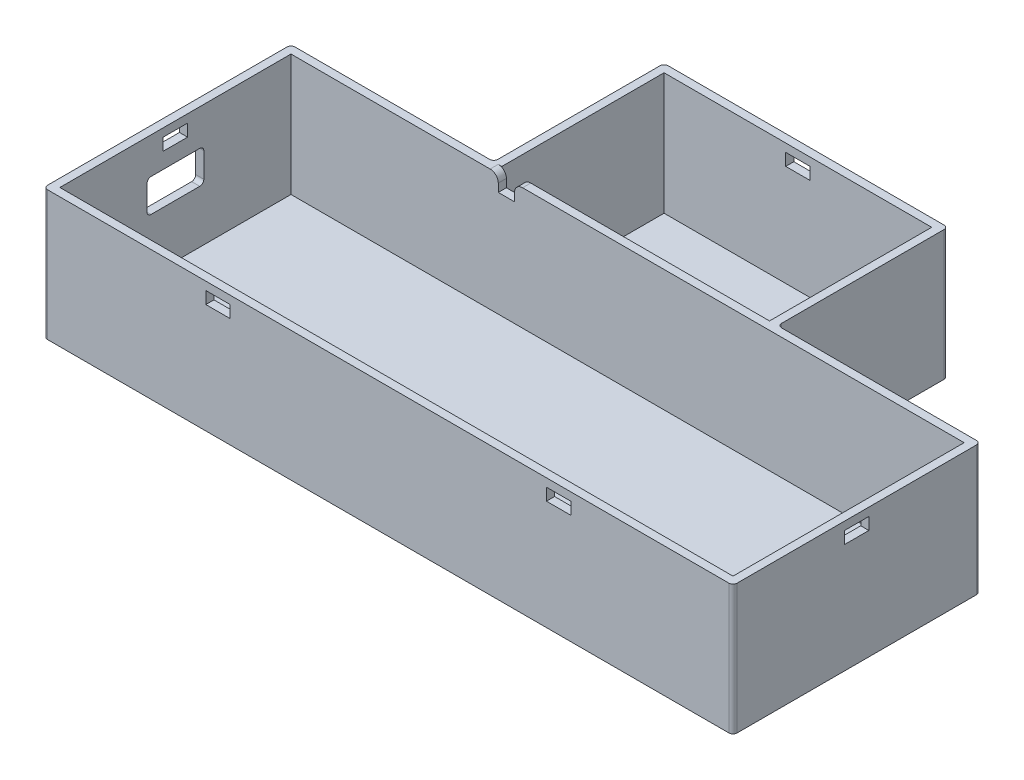
SolidWorks part; units mm, degrees
ref_plane "Front Plane" through (0, 0, 0) normal (0, 0, 1) x (1, 0, 0)
ref_plane "Top Plane" through (0, 0, 0) normal (0, 1, 0) x (1, 0, 0)
ref_plane "Right Plane" through (0, 0, 0) normal (1, 0, 0) x (0, 0, -1)
sketch "Sketch1" plane through (0, 0, 0) normal (0, 1, 0) x (1, 0, 0)
  line L1 (0, 0) -> (170, 0)
  line L2 (0, 0) -> (0, -61)
  line L3 (0, -61) -> (170, -61)
  line L4 (170, 0) -> (170, -61)
  dimension "D1" = 170
  dimension "D2" = 61
extrude "Boss-Extrude1" add sketch "Sketch1" along normal blind 2
sketch "Sketch2" plane through (0, 2, 0) normal (0, 1, 0) x (1, 0, 0)
  line L0 (170, -61) -> (170, 0) construction
  line L1 (0, 0) -> (170, 0)
  line L2 (0, 0) -> (0, -2)
  line L3 (0, -2) -> (170, -2)
  line L4 (170, 0) -> (170, -2)
  dimension "D1" = 2
extrude "Boss-Extrude2" add sketch "Sketch2" along normal blind 17 contours L3 L4 L1 L2
sketch "Sketch3" plane through (0, 2, 0) normal (0, 1, 0) x (1, 0, 0)
  line L0 (0, -2) -> (170, -2) construction
  line L1 (0, -61) -> (2, -61)
  line L2 (0, -61) -> (0, -2)
  line L3 (0, -2) -> (2, -2)
  line L4 (2, -61) -> (2, -2)
  line L5 (0, -2) -> (170, -2) construction
  line L6 (170, -61) -> (168, -61)
  line L7 (170, -61) -> (170, -2)
  line L8 (170, -2) -> (168, -2)
  line L9 (168, -61) -> (168, -2)
  line L11 (2, -61) -> (168, -61)
  line L12 (2, -61) -> (2, -59)
  line L13 (2, -59) -> (168, -59)
  line L14 (168, -61) -> (168, -59)
  line M6 (170, -2) -> (0, -2)
  line M7 (0, -2) -> (0, -61)
  line M8 (0, -61) -> (170, -61)
  line M9 (170, -61) -> (170, -2)
  dimension "D1" = 2
  dimension "D2" = 2
  dimension "D3" = 2
extrude "Boss-Extrude3" add sketch "Sketch3" along normal blind 17 contours L4 M8 M6 M7 | L9 M8 M9 M6 | L13 L4 L9 M8
sketch "Sketch4" plane through (0, 0, 0) normal (0, 0, -1) x (-1, 0, 0)
  line L0 (-170, 0) -> (0, 0) construction
  line L1 (-120, -2) -> (-50, -2)
  line L2 (-120, -2) -> (-120, 2)
  line L3 (-120, 2) -> (-50, 2)
  line L4 (-50, -2) -> (-50, 2)
  line L5 (-120, -2) -> (-50, 2) construction
  line L6 (-120, 2) -> (-50, -2) construction
  line L7 (-50, 0) -> (-120, 0)
  point P0 (-85, 0)
  line M5 (-170, 0) -> (0, 0)
  dimension "D1" = 4
  dimension "D2" = 70
extrude "Boss-Extrude4" add sketch "Sketch4" along normal blind 42 contours L4 L3 L2 M5
sketch "Sketch5" plane through (0, 0, 0) normal (0, 0, -1) x (-1, 0, 0)
  line L0 (0, 19) -> (-170, 19) construction
  line L1 (-57.1169, 23) -> (-53.1169, 23)
  line L2 (-57.1169, 23) -> (-57.1169, 15)
  line L3 (-57.1169, 15) -> (-53.1169, 15)
  line L4 (-53.1169, 23) -> (-53.1169, 15)
  line L5 (-57.1169, 23) -> (-53.1169, 15) construction
  line L6 (-57.1169, 15) -> (-53.1169, 23) construction
  point P0 (-55.1169, 19)
  dimension "D1" = 8
  dimension "D2" = 4
extrude "Cut-Extrude1" cut sketch "Sketch5" against normal blind 39 contours L3 L4 L1 L2
fillet "Fillet1" radius 2 2 edges at (53.1169, 19, 1) (57.1169, 19, 1)
sketch "Sketch6" plane through (0, 2, 0) normal (0, 1, 0) x (1, 0, 0)
  line L0 (59.1169, 0) -> (170, 0) construction
  line L1 (120, 42) -> (118, 42)
  line L2 (120, 42) -> (120, 0)
  line L3 (120, 0) -> (118, 0)
  line L4 (118, 42) -> (118, 0)
  line L5 (0, 0) -> (51.1169, 0) construction
  line L6 (50, 42) -> (52, 42)
  line L7 (50, 42) -> (50, 0)
  line L8 (50, 0) -> (52, 0)
  line L9 (52, 42) -> (52, 0)
  dimension "D1" = 2
  dimension "D2" = 2
extrude "Boss-Extrude5" add sketch "Sketch6" along normal blind 17 contours L4 L3 L2 L1
sketch "Sketch9" plane through (0, 2, 0) normal (0, 1, 0) x (1, 0, 0)
  line L0 (118, 0) -> (50, 0) construction
  line L1 (50, 42) -> (52, 42)
  line L2 (50, 42) -> (50, 0)
  line L3 (50, 0) -> (52, 0)
  line L4 (52, 42) -> (52, 0)
  line L6 (118, 42) -> (52, 42)
  line L7 (118, 42) -> (118, 40)
  line L8 (118, 40) -> (52, 40)
  line L9 (52, 42) -> (52, 40)
  line M3 (50, 0) -> (118, 0)
  line M4 (118, 0) -> (118, 42)
  line M5 (118, 42) -> (50, 42)
  line M6 (50, 42) -> (50, 0)
  dimension "D1" = 2
  dimension "D2" = 2
extrude "Boss-Extrude6" add sketch "Sketch9" along normal blind 17 contours L4 M5 M6 M3 | L8 L4 M4 M5
sketch "Sketch10" plane through (0, 0, 61) normal (0, 0, 1) x (1, 0, 0)
  line L0 (0, 19) -> (0, 0) construction
  line L1 (40, 17) -> (46, 17)
  line L2 (40, 17) -> (40, 14)
  line L3 (40, 14) -> (46, 14)
  line L4 (46, 17) -> (46, 14)
  line L5 (0, 19) -> (170, 19) construction
  line L6 (85, 19) -> (85, 0) construction
  line L7 (0, 0) -> (170, 0) construction
  line L8 (170, 19) -> (170, 0) construction
  line L9 (124, 14) -> (130, 14)
  line L10 (124, 14) -> (124, 17)
  line L11 (124, 17) -> (130, 17)
  line L12 (130, 14) -> (130, 17)
  point P16 (130, 15.5)
  dimension "D1" = 6
  dimension "D2" = 3
  dimension "D3" = 40
  dimension "D4" = 2
  dimension "D5" = 3
  dimension "D6" = 6
  dimension "D7" = 2
  dimension "D8" = 40
extrude "Cut-Extrude2" cut sketch "Sketch10" against normal blind 10
sketch "Sketch11" plane through (0, 0, 0) normal (-1, 0, 0) x (0, 0, 1)
  line L0 (0, 0) -> (0, 19) construction
  line L1 (27.5, 17) -> (33.5, 17)
  line L2 (27.5, 17) -> (27.5, 14)
  line L3 (27.5, 14) -> (33.5, 14)
  line L4 (33.5, 17) -> (33.5, 14)
  line L5 (0, 19) -> (61, 19) construction
  dimension "D1" = 3
  dimension "D2" = 6
  dimension "D3" = 27.5
  dimension "D4" = 2
extrude "Cut-Extrude3" cut sketch "Sketch11" against normal blind 10
sketch "Sketch12" plane through (0, 0, -42) normal (0, 0, -1) x (-1, 0, 0)
  line L0 (-50, 0) -> (-50, 19) construction
  line L1 (-88, 17) -> (-82, 17)
  line L2 (-88, 17) -> (-88, 14)
  line L3 (-88, 14) -> (-82, 14)
  line L4 (-82, 17) -> (-82, 14)
  line L5 (-120, 19) -> (-50, 19) construction
  dimension "D1" = 3
  dimension "D2" = 6
  dimension "D3" = 32
  dimension "D4" = 2
extrude "Cut-Extrude4" cut sketch "Sketch12" against normal blind 10
sketch "Sketch13" plane through (170, 0, 0) normal (1, 0, 0) x (0, 0, -1)
  line L0 (-33.5, 17) -> (-27.5, 17) construction
  line L1 (-33.5, 17) -> (-27.5, 17)
  line L2 (-27.5, 14) -> (-33.5, 14) construction
  line L3 (-27.5, 14) -> (-33.5, 14)
  line L12 (-27.5, 17) -> (-27.5, 14) construction
  line L13 (-27.5, 17) -> (-27.5, 14)
  line L14 (-33.5, 14) -> (-33.5, 17) construction
  line L15 (-33.5, 14) -> (-33.5, 17)
extrude "Cut-Extrude5" cut sketch "Sketch13" against normal blind 10 contours L15 L1 L13 L3
sketch "Sketch14" plane through (0, 0, 0) normal (0, -1, 0) x (1, 0, 0)
  line L0 (0, 61) -> (0, 0)
  line L1 (0, 0) -> (50, 0)
  line L2 (50, 0) -> (50, -42)
  line L3 (50, -42) -> (120, -42)
  line L4 (120, -42) -> (120, 0)
  line L5 (120, 0) -> (170, 0)
  line L6 (170, 0) -> (170, 61)
  line L7 (170, 61) -> (0, 61)
extrude "Cut-Extrude6" cut sketch "Sketch14" against normal blind 2
sketch "Sketch15" plane through (0, 2, 0) normal (0, -1, 0) x (1, 0, 0)
  line L0 (118, 0) -> (52, 0) construction
  line L1 (118, -40) -> (118, 0) construction
  line L2 (52, -40) -> (52, 0) construction
  line L3 (118, -40) -> (52, -40) construction
  line L4 (2, 59) -> (168, 59) construction
  line L5 (2, 59) -> (2, 2) construction
  line L6 (2, 2) -> (168, 2) construction
  line L7 (168, 59) -> (168, 2) construction
  line L8 (170, 61) -> (0, 61)
  line L9 (0, 61) -> (0, 0)
  line L10 (0, 0) -> (50, 0)
  line L11 (50, 0) -> (50, -42)
  line L12 (50, -42) -> (120, -42)
  line L13 (120, -42) -> (120, 0)
  line L14 (120, 0) -> (170, 0)
  line L15 (170, 0) -> (170, 61)
  line L16 (170, 61) -> (0, 61)
  line L17 (0, 61) -> (0, 0)
  line L18 (0, 0) -> (50, 0)
  line L19 (50, 0) -> (50, -42)
  line L20 (50, -42) -> (120, -42)
  line L21 (120, -42) -> (120, 0)
  line L22 (120, 0) -> (170, 0)
  line L23 (170, 0) -> (170, 61)
  line L24 (118, 0) -> (52, 0)
  line L25 (118, -40) -> (118, 0)
  line L26 (52, -40) -> (52, 0)
  line L27 (118, -40) -> (52, -40)
  line L28 (2, 59) -> (168, 59)
  line L29 (2, 59) -> (2, 2)
  line L30 (2, 2) -> (168, 2)
  line L31 (168, 59) -> (168, 2)
  dimension "D1" = 0
extrude "Boss-Extrude7" add sketch "Sketch15" along normal blind 13
sketch "Sketch16" plane through (0, -11, 0) normal (0, -1, 0) x (1, 0, 0)
  line L0 (120, -42) -> (120, 0)
  line L1 (50, -42) -> (120, -42) construction
  line L2 (120, -42) -> (120, 0) construction
  line L3 (120, 0) -> (170, 0)
  line L4 (170, 0) -> (170, 61)
  line L5 (170, 61) -> (0, 61)
  line L6 (0, 61) -> (0, 0)
  line L7 (0, 0) -> (50, 0)
  line L8 (50, 0) -> (50, -42)
  line L9 (50, -42) -> (120, -42)
extrude "Boss-Extrude8" add sketch "Sketch16" along normal blind 2
sketch "Sketch17" plane through (0, 0, 0) normal (-1, 0, 0) x (0, 0, 1)
  line L0 (61, 19) -> (61, -13) construction
  line L1 (23.5, 10.1) -> (37.5, 10.1)
  line L2 (23.5, 10.1) -> (23.5, 2)
  line L3 (23.5, 2) -> (37.5, 2)
  line L4 (37.5, 10.1) -> (37.5, 2)
  line L5 (61, -13) -> (0, -13) construction
  dimension "D1" = 14
  dimension "D2" = 23.5
  dimension "D3" = 8.1
  dimension "D4" = 15
extrude "Cut-Extrude7" cut sketch "Sketch17" against normal blind 2
fillet "Fillet2" radius 1 8 edges at (170, 3, 61) (170, 3, 0) (120, 3, 0) (120, 3, -42) (0, 3, 61) (0, 3, 0) (50, 3, 0) (50, 3, -42)
fillet "Fillet3" radius 1 4 edges at (1, 2, 37.5) (1, 10.1, 37.5) (1, 10.1, 23.5) (1, 2, 23.5)
